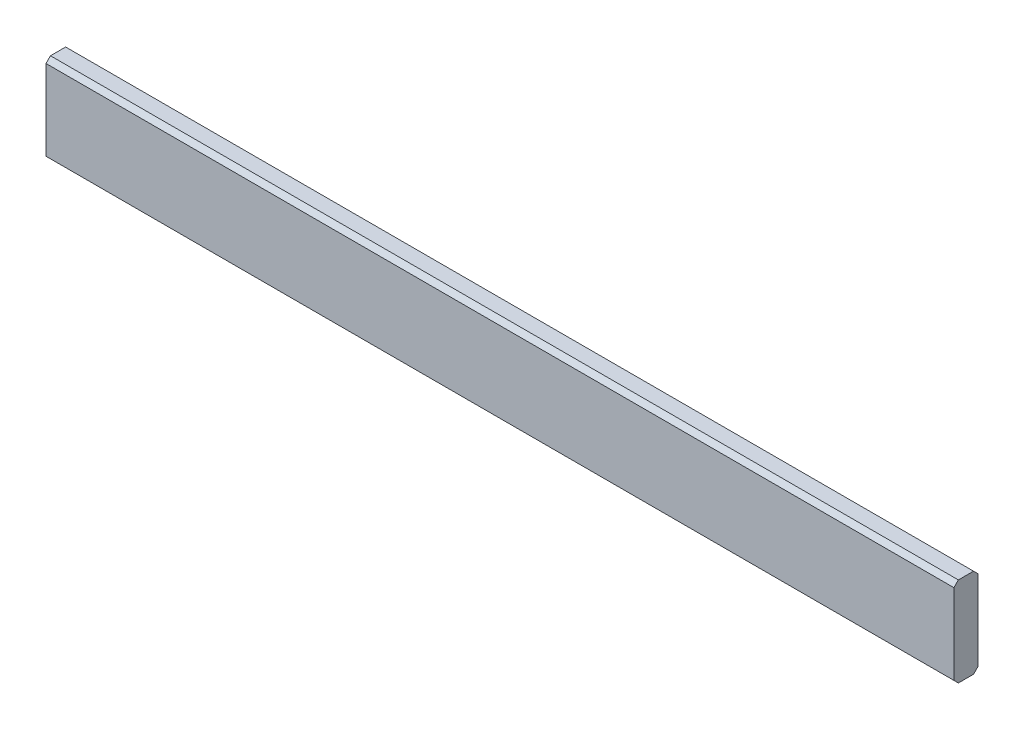
SolidWorks part; units mm, degrees
ref_plane "Plan de face" through (0, 0, 0) normal (0, 0, 1) x (1, 0, 0)
ref_plane "Plan de dessus" through (0, 0, 0) normal (0, 1, 0) x (1, 0, 0)
ref_plane "Plan de droite" through (0, 0, 0) normal (1, 0, 0) x (0, 0, -1)
sketch "Esquisse1" plane through (0, 0, 0) normal (0, 0, 1) x (1, 0, 0)
  line L1 (0, 0) -> (1017, 0)
  line L2 (0, 0) -> (0, 100)
  line L3 (0, 100) -> (1017, 100)
  line L4 (1017, 0) -> (1017, 100)
  dimension "D1" = 100
  dimension "D2" = 1017
extrude "Boss.-Extru.1" add sketch "Esquisse1" along normal blind 27
chamfer "Chanfrein1" distance 5 angle 45 4 edges at (508.5, 0, 0) (508.5, 0, 27) (508.5, 100, 0) (508.5, 100, 27)
